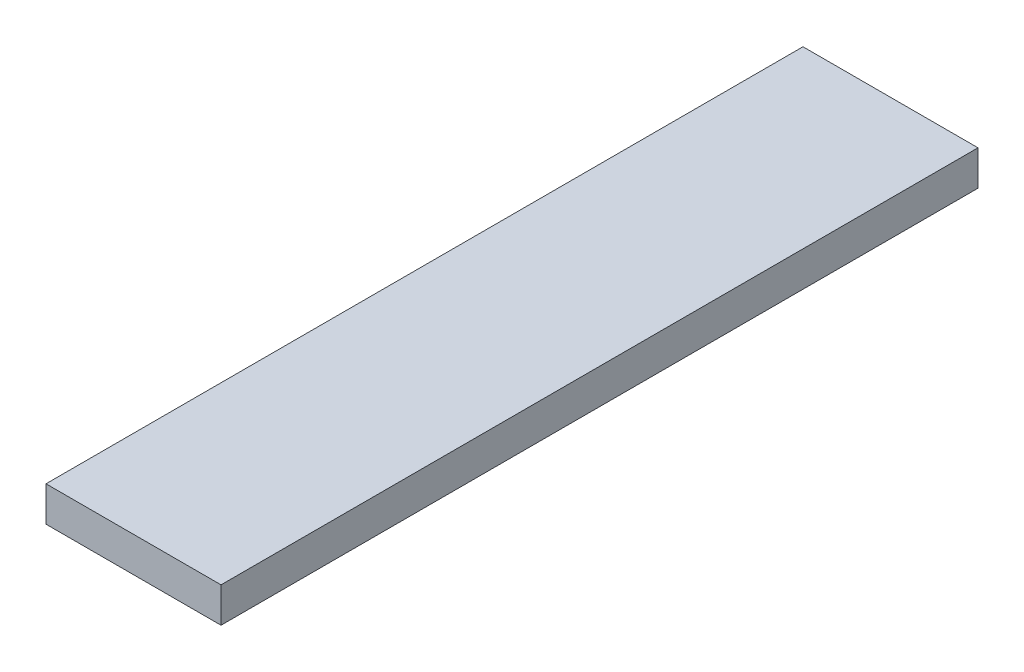
SolidWorks part; units mm, degrees
material "Сосна"
ref_plane "Спереди" through (0, 0, 0) normal (0, 0, 1) x (1, 0, 0)
ref_plane "Сверху" through (0, 0, 0) normal (0, 1, 0) x (1, 0, 0)
ref_plane "Справа" through (0, 0, 0) normal (1, 0, 0) x (0, 0, -1)
sketch "Эскиз1" plane through (0, 0, 0) normal (0, 0, 1) x (1, 0, 0)
  line L1 (0, 0) -> (-200, 0)
  line L2 (0, 0) -> (0, 40)
  line L3 (0, 40) -> (-200, 40)
  line L4 (-200, 0) -> (-200, 40)
  dimension "D1" = 40
  dimension "D2" = 200
extrude "Бобышка-Вытянуть1" add sketch "Эскиз1" against normal offset from surface (865 mm away) 5
